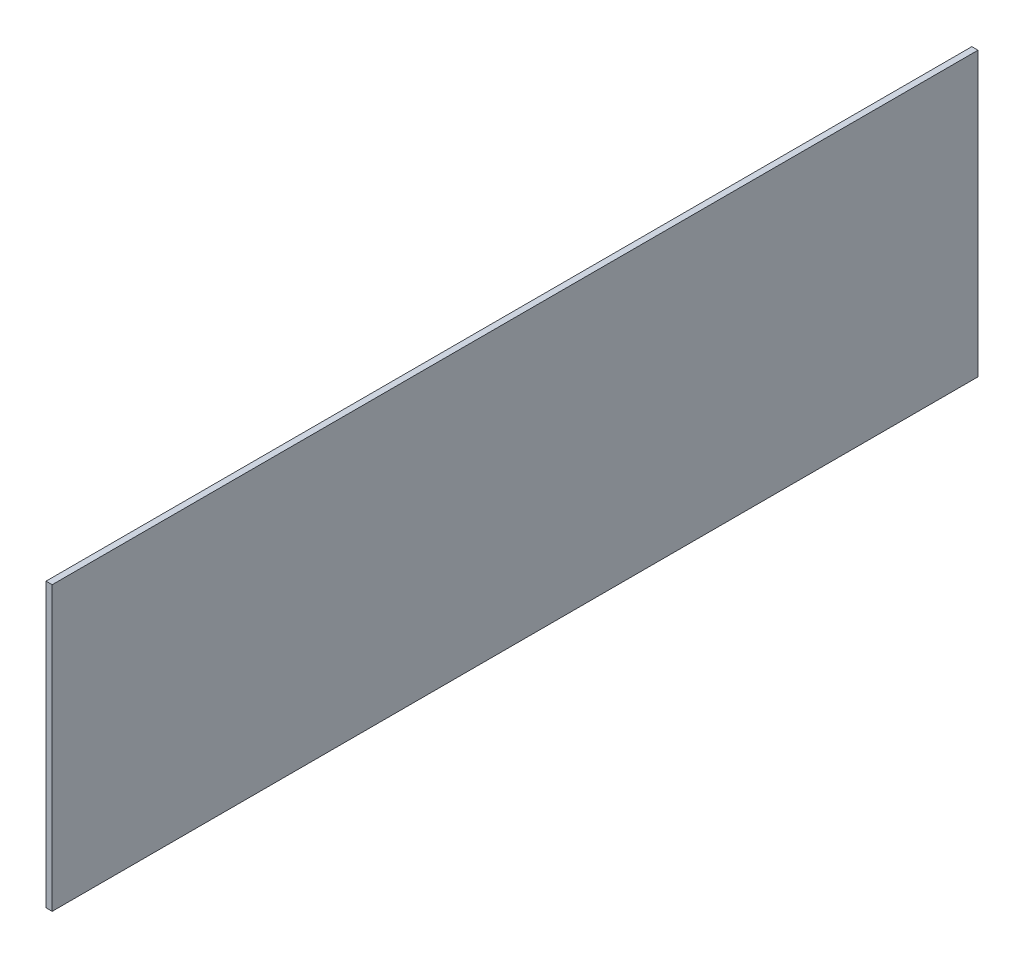
SolidWorks part; units mm, degrees
ref_plane "Front Plane" through (0, 0, 0) normal (0, 0, 1) x (1, 0, 0)
ref_plane "Top Plane" through (0, 0, 0) normal (0, 1, 0) x (1, 0, 0)
ref_plane "Right Plane" through (0, 0, 0) normal (1, 0, 0) x (0, 0, -1)
sketch "Sketch1" plane through (0, 0, 0) normal (0, 0, 1) x (1, 0, 0)
  line L1 (-50.8235, 130.5882) -> (-38.8235, 130.5882)
  line L2 (-50.8235, 130.5882) -> (-50.8235, -419.4118)
  line L3 (-50.8235, -419.4118) -> (-38.8235, -419.4118)
  line L4 (-38.8235, 130.5882) -> (-38.8235, -419.4118)
  dimension "D1" = 12
  dimension "D2" = 550
extrude "Boss-Extrude1" add sketch "Sketch1" along normal blind 1800
